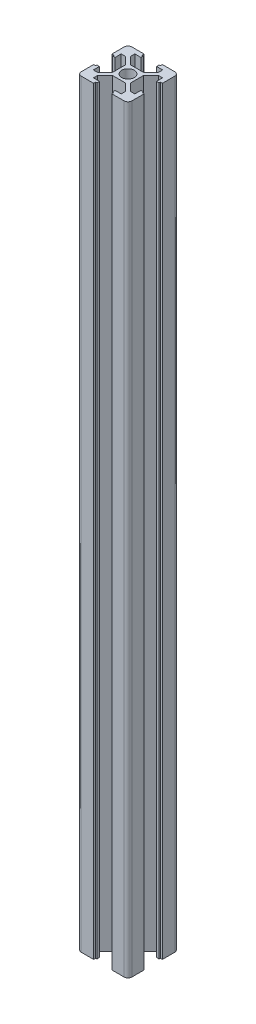
SolidWorks part; units mm, degrees
ref_plane "前视基准面" through (0, 0, 0) normal (0, 0, 1) x (1, 0, 0)
ref_plane "上视基准面" through (0, 0, 0) normal (0, 1, 0) x (1, 0, 0)
ref_plane "右视基准面" through (0, 0, 0) normal (1, 0, 0) x (0, 0, -1)
other "Configuration Table"
sketch "草图1" plane through (0, 0, 0) normal (0, 1, 0) x (1, 0, 0)
  line L0 (-5.8258, 3.4539) -> (-5.8258, 6.5539) construction
  line L1 (-5.8258, 5.9932) -> (-5.8258, 0.9145)
  line L2 (0.3135, 7.0539) -> (-4.7652, 7.0539)
  line L3 (1.3742, 0.9145) -> (1.3742, 5.9932)
  line L4 (-4.7652, -0.1461) -> (0.3135, -0.1461)
  line L5 (-12.2258, 3.4539) -> (7.7742, 3.4539) construction
  line L6 (-2.2258, 13.4539) -> (-2.2258, -6.5461) construction
  line L7 (-12.2258, 13.4539) -> (-2.2258, 3.4539) construction
  line L8 (-12.2258, 7.0539) -> (-5.8258, 7.0539) construction
  line L9 (-11.4258, 6.5539) -> (-5.3258, 6.5539) construction
  line L10 (-10.4258, 8.9539) -> (-7.7258, 8.9539) construction
  line L11 (-8.7865, 8.9539) -> (-5.8258, 5.9932) construction
  line L12 (-12.2258, 11.9539) -> (-12.2258, 7.0539)
  line L13 (-12.2258, 7.0539) -> (-11.4258, 7.0539)
  line L14 (-11.4258, 7.0539) -> (-11.4258, 6.5539)
  line L15 (-11.4258, 6.5539) -> (-10.4258, 6.5539)
  line L16 (-10.4258, 6.5539) -> (-10.4258, 8.9539)
  line L17 (-10.4258, 8.9539) -> (-8.7865, 8.9539)
  line L18 (-8.7865, 8.9539) -> (-5.8258, 5.9932)
  line L19 (-5.3258, 12.6539) -> (-5.3258, 11.6539)
  line L20 (-5.8258, 12.6539) -> (-5.3258, 12.6539)
  line L21 (-5.8258, 13.4539) -> (-5.8258, 12.6539)
  line L22 (-10.7258, 13.4539) -> (-5.8258, 13.4539)
  line L23 (-5.3258, 11.6539) -> (-7.7258, 11.6539)
  line L24 (-7.7258, 11.6539) -> (-7.7258, 10.0145)
  line L25 (-7.7258, 10.0145) -> (-4.7652, 7.0539)
  line L26 (7.7742, 13.4539) -> (-2.2258, 3.4539) construction
  line L27 (3.2742, 10.0145) -> (0.3135, 7.0539)
  line L28 (3.2742, 11.6539) -> (3.2742, 10.0145)
  line L29 (0.8742, 11.6539) -> (3.2742, 11.6539)
  line L30 (0.8742, 12.6539) -> (0.8742, 11.6539)
  line L31 (1.3742, 12.6539) -> (0.8742, 12.6539)
  line L32 (1.3742, 13.4539) -> (1.3742, 12.6539)
  line L33 (6.2742, 13.4539) -> (1.3742, 13.4539)
  line L34 (7.7742, 11.9539) -> (7.7742, 7.0539)
  line L35 (7.7742, 7.0539) -> (6.9742, 7.0539)
  line L36 (6.9742, 7.0539) -> (6.9742, 6.5539)
  line L37 (6.9742, 6.5539) -> (5.9742, 6.5539)
  line L38 (5.9742, 6.5539) -> (5.9742, 8.9539)
  line L39 (5.9742, 8.9539) -> (4.3348, 8.9539)
  line L40 (4.3348, 8.9539) -> (1.3742, 5.9932)
  line L41 (7.7742, -6.5461) -> (-2.2258, 3.4539) construction
  line L42 (4.3348, -2.0461) -> (1.3742, 0.9145)
  line L43 (5.9742, -2.0461) -> (4.3348, -2.0461)
  line L44 (5.9742, 0.3539) -> (5.9742, -2.0461)
  line L45 (6.9742, 0.3539) -> (5.9742, 0.3539)
  line L46 (6.9742, -0.1461) -> (6.9742, 0.3539)
  line L47 (7.7742, -0.1461) -> (6.9742, -0.1461)
  line L48 (7.7742, -5.0461) -> (7.7742, -0.1461)
  line L49 (6.2742, -6.5461) -> (1.3742, -6.5461)
  line L50 (1.3742, -6.5461) -> (1.3742, -5.7461)
  line L51 (1.3742, -5.7461) -> (0.8742, -5.7461)
  line L52 (0.8742, -5.7461) -> (0.8742, -4.7461)
  line L53 (0.8742, -4.7461) -> (3.2742, -4.7461)
  line L54 (3.2742, -4.7461) -> (3.2742, -3.1068)
  line L55 (3.2742, -3.1068) -> (0.3135, -0.1461)
  line L56 (-12.2258, -6.5461) -> (-2.2258, 3.4539) construction
  line L57 (-7.7258, -3.1068) -> (-4.7652, -0.1461)
  line L58 (-7.7258, -4.7461) -> (-7.7258, -3.1068)
  line L59 (-5.3258, -4.7461) -> (-7.7258, -4.7461)
  line L60 (-5.3258, -5.7461) -> (-5.3258, -4.7461)
  line L61 (-5.8258, -5.7461) -> (-5.3258, -5.7461)
  line L62 (-5.8258, -6.5461) -> (-5.8258, -5.7461)
  line L63 (-10.7258, -6.5461) -> (-5.8258, -6.5461)
  line L64 (-12.2258, -5.0461) -> (-12.2258, -0.1461)
  line L65 (-12.2258, -0.1461) -> (-11.4258, -0.1461)
  line L66 (-11.4258, -0.1461) -> (-11.4258, 0.3539)
  line L67 (-11.4258, 0.3539) -> (-10.4258, 0.3539)
  line L68 (-10.4258, 0.3539) -> (-10.4258, -2.0461)
  line L69 (-10.4258, -2.0461) -> (-8.7865, -2.0461)
  line L70 (-8.7865, -2.0461) -> (-5.8258, 0.9145)
  arc A0 (-12.2258, 11.9539) -> (-10.7258, 13.4539) centre (-10.7258, 11.9539) cw
  circle A1 centre (-2.2258, 3.4539) radius 2.5
  arc A2 (6.2742, 13.4539) -> (7.7742, 11.9539) centre (6.2742, 11.9539) cw
  arc A3 (7.7742, -5.0461) -> (6.2742, -6.5461) centre (6.2742, -5.0461) cw
  arc A4 (-10.7258, -6.5461) -> (-12.2258, -5.0461) centre (-10.7258, -5.0461) cw
  point P13 (-2.2258, 3.4539)
  point P84 (-2.2258, 3.4539)
  dimension "D8" = 1.5
  dimension "D9" = 5
  dimension "D1" = 20
  dimension "D2" = 6.2
  dimension "D3" = 7.2
  dimension "D4" = 11
  dimension "D5" = 1.5
  dimension "D6" = 0.8
  dimension "D7" = 1.8
  dimension "D10" = 7.2
extrude "凸台-拉伸1" add sketch "草图1" along normal blind 300
sketch "草图2" plane through (0, 0, 0.1461) normal (0, 0, 1) x (1, 0, 0)
  line L0 (-2.2258, 195) -> (49947.7742, 195) construction
  line L1 (-52.2258, 192.4607) -> (-52.2258, 197.5393) construction
  line L2 (-2.2258, 300) -> (-2.2258, 195) construction
  line L3 (-4.7652, 300) -> (0.3135, 300) construction
  line L5 (-12.2258, 150) -> (49987.7742, 150) construction
  line L6 (-12.2258, 300) -> (-12.2258, 0) construction
  line L7 (7.7742, 300) -> (7.7742, 0) construction
  line L8 (97.7742, 320) -> (97.7742, -49680) construction
  line L9 (177.7742, 320) -> (17.7742, 320) construction
  circle A0 centre (-2.2258, 195) radius 1.75
  circle A1 centre (-2.2258, 105) radius 1.75
  circle A2 centre (197.7742, 105) radius 1.75
  circle A3 centre (197.7742, 195) radius 1.75
  point P4 (-52.2258, 195)
  point P9 (-2.2258, 300)
  point P14 (-12.2258, 150)
  point P17 (7.7742, 150)
  point P22 (97.7742, 320)
  dimension "D1" = 3.5
extrude "切除-拉伸1" cut sketch "草图2" against normal blind 10
